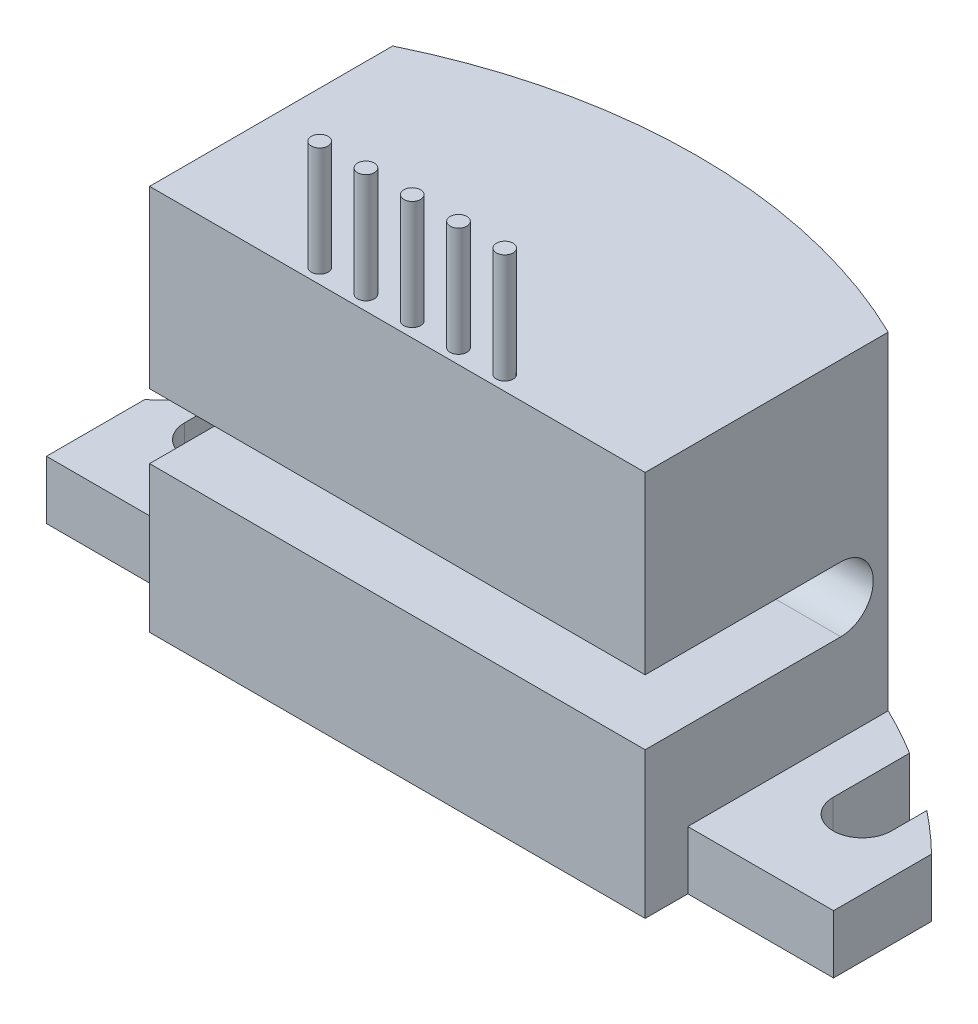
SolidWorks part; units mm, degrees
ref_plane "Front Plane" through (0, 0, 0) normal (0, 0, 1) x (1, 0, 0)
ref_plane "Top Plane" through (0, 0, 0) normal (0, 1, 0) x (1, 0, 0)
ref_plane "Right Plane" through (0, 0, 0) normal (1, 0, 0) x (0, 0, -1)
sketch "Sketch1" plane through (0, 0, 0) normal (0, 1, 0) x (1, 0, 0)
  line L0 (-10.8, 11.118) -> (-10.8, 8.428)
  line L1 (-10.8, 8.428) -> (-6.8, 8.428)
  line L2 (-6.8, 8.428) -> (-6.8, 7.258)
  line L3 (-6.8, 7.258) -> (6.8, 7.258)
  line L4 (6.8, 7.258) -> (6.8, 8.428)
  line L5 (6.8, 8.428) -> (10.8, 8.428)
  line L6 (10.8, 8.428) -> (10.8, 11.118)
  arc A0 (10.8, 11.118) -> (-10.8, 11.118) centre (0, 0) ccw
  dimension "D1" = 31
  dimension "D2" = 0
  dimension "D3" = 4
  dimension "D4" = 4
  dimension "D5" = 13.6
  dimension "D6" = 1.17
  dimension "D7" = 2.69
  dimension "D8" = 2.69
extrude "Boss-Extrude1" add sketch "Sketch1" along normal blind 14.4
sketch "Sketch2" plane through (0, 0, 0) normal (0, -1, 0) x (1, 0, 0)
  line L0 (-6.8, -7.258) -> (6.8, -7.258) construction
  line L1 (-6.8, -8.428) -> (-6.8, -7.258) construction
  line L2 (6.8, -7.258) -> (6.8, -8.428) construction
  circle A0 centre (-6.4, -10.948) radius 1
  circle A1 centre (6.4, -10.948) radius 1
  circle A2 centre (0, -10.948) radius 11.8194
  dimension "D1" = 2
  dimension "D2" = 2
  dimension "D3" = 3.69
  dimension "D4" = 3.69
  dimension "D5" = 0.4
  dimension "D6" = 0.4
extrude "Cut-Extrude1" cut sketch "Sketch2" against normal blind 0.8 contours A2 | A1 | A0
sketch "Sketch3" plane through (0, 14.4, 0) normal (0, 1, 0) x (1, 0, 0)
  line L0 (-6.8, 8.428) -> (-6.8, 13.9287)
  line L1 (-6.8, 13.9287) -> (-13.3426, 13.9287)
  line L2 (-13.3426, 13.9287) -> (-13.3426, 8.428)
  line L3 (-13.3426, 8.428) -> (-6.8, 8.428)
  line L4 (6.8, 8.428) -> (6.8, 13.9287)
  line L5 (6.8, 13.9287) -> (12.6415, 13.9287)
  line L6 (12.6415, 13.9287) -> (12.6415, 8.428)
  line L7 (12.6415, 8.428) -> (6.8, 8.428)
  arc A0 (10.8, 11.118) -> (-10.8, 11.118) centre (0, 0) ccw construction
extrude "Cut-Extrude2" cut sketch "Sketch3" against normal blind 12
sketch "Sketch4" plane through (0, 0.8, 0) normal (0, -1, 0) x (1, 0, 0)
  line L0 (10.8, -11.118) -> (10.8, -8.428) construction
  line L1 (10.8, -8.428) -> (6.8, -8.428) construction
  line L2 (-6.8, -8.428) -> (-10.8, -8.428) construction
  line L3 (9.7, -11.118) -> (9.7, -12.0897)
  line L4 (8.1, -11.118) -> (8.1, -13.2151)
  line L5 (8.1, -13.2151) -> (9.7, -13.2151)
  line L6 (9.7, -13.2151) -> (9.7, -12.0897)
  line L7 (-8.1, -11.118) -> (-8.1, -13.2151)
  line L8 (-8.1, -13.2151) -> (-9.7, -13.2151)
  line L9 (-9.7, -13.2151) -> (-9.7, -11.118)
  arc A0 (9.7, -11.118) -> (8.1, -11.118) centre (8.9, -11.118) ccw
  arc A1 (-8.1, -11.118) -> (-9.7, -11.118) centre (-8.9, -11.118) ccw
  arc A2 (-10.8, -11.118) -> (10.8, -11.118) centre (0, 0) ccw construction
  point P6 (10.8, -9.773)
  dimension "D1" = 1.6
  dimension "D2" = 1.6
  dimension "D5" = 2.69
  dimension "D6" = 2.69
  dimension "D3" = 17.8
  dimension "D4" = 1.9
extrude "Cut-Extrude3" cut sketch "Sketch4" against normal through all
sketch "Sketch5" plane through (-6.8, 0, 0) normal (-1, 0, 0) x (0, 0, 1)
  line L0 (-7.258, 0.8) -> (-8.428, 0.8) construction
  line L1 (-12.628, 6.59) -> (-7.258, 6.59)
  line L2 (-7.258, 14.4) -> (-7.258, 0.8) construction
  line L3 (-7.258, 6.59) -> (-7.258, 4.81)
  line L4 (-7.258, 4.81) -> (-12.628, 4.81)
  arc A0 (-12.628, 6.59) -> (-12.628, 4.81) centre (-12.628, 5.7) ccw
  dimension "D1" = 1.78
  dimension "D2" = 4.9
  dimension "D3" = 5.37
extrude "Cut-Extrude4" cut sketch "Sketch5" against normal through all
sketch "Sketch6" plane through (0, 14.4, 0) normal (0, 1, 0) x (1, 0, 0)
  line L0 (0, 17.8181) -> (0, 5.1616) construction
  line L1 (-4.1228, 7.6663) -> (4.5439, 7.6663) construction
  circle A0 centre (0, 7.6663) radius 0.23
  circle A1 centre (1.27, 7.6663) radius 0.23
  circle A2 centre (2.54, 7.6663) radius 0.23
  circle A3 centre (-1.27, 7.6663) radius 0.23
  circle A4 centre (-2.54, 7.6663) radius 0.23
  circle A5 centre (0, 7.6663) radius 9.6553
  dimension "D1" = 0.46
  dimension "D2" = 0.46
  dimension "D3" = 0.46
  dimension "D4" = 0.46
  dimension "D5" = 0.46
  dimension "D7" = 1.27
  dimension "D8" = 1.27
  dimension "D9" = 1.27
  dimension "D6" = 1.27
extrude "Cut-Extrude5" cut sketch "Sketch6" against normal blind 3
